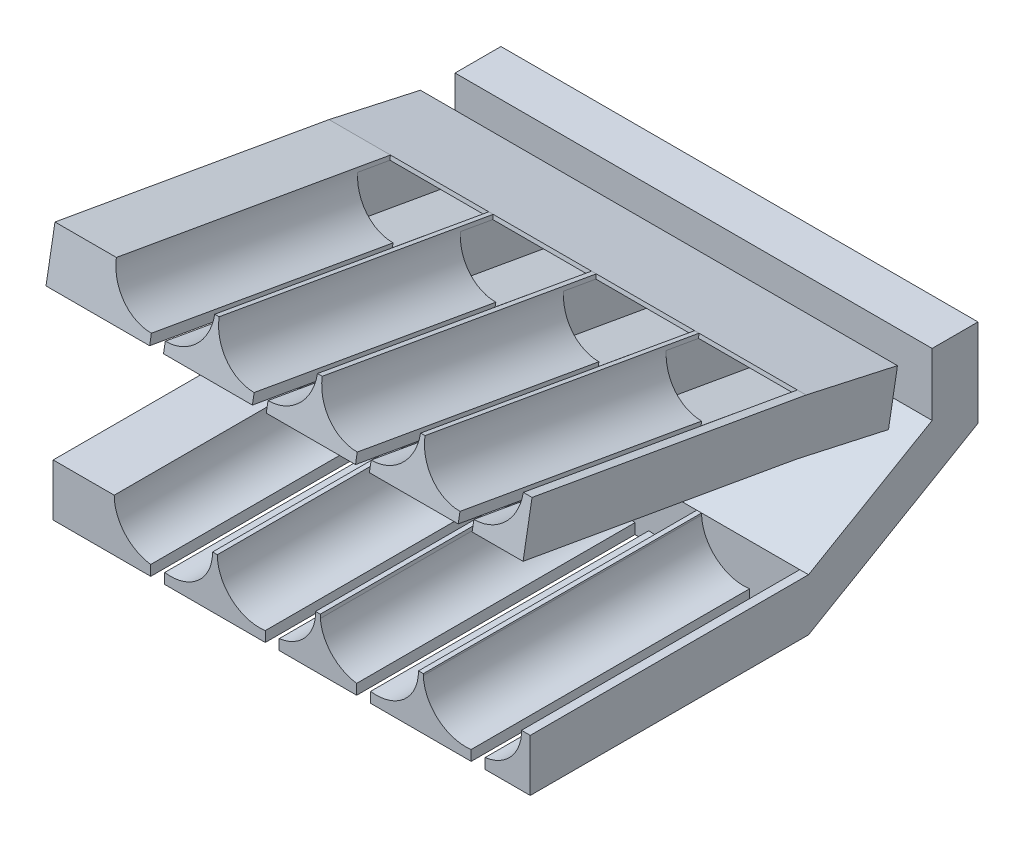
SolidWorks part; units mm, degrees
ref_plane "Front Plane" through (0, 0, 0) normal (0, 0, 1) x (1, 0, 0)
ref_plane "Top Plane" through (0, 0, 0) normal (0, 1, 0) x (1, 0, 0)
ref_plane "Right Plane" through (0, 0, 0) normal (1, 0, 0) x (0, 0, -1)
sketch "Sketch2" plane through (0, 0, 0) normal (1, 0, 0) x (0, 0, -1)
  line L1 (-68.9365, 12.1554) -> (-66.6791, 24.9579)
  line L2 (-66.6791, 24.9579) -> (2.2574, 12.8025)
  line L3 (2.2574, 12.8025) -> (0, 0)
  line L4 (0, 0) -> (-68.9365, 12.1554)
  point P3 (1.1287, 6.4013)
  dimension "D1" = 13
  dimension "D2" = 70
extrude "Boss-Extrude1" add sketch "Sketch2" along normal blind 120
sketch "Sketch4" plane through (0, 0, 0) normal (0, -0.1736, -0.9848) x (-1, 0, 0)
  line L0 (-93.0728, 13) -> (-92.5195, 13)
  line L1 (-120, 13) -> (0, 13) construction
  line L2 (-120, 0) -> (0, 0) construction
  line L3 (-105.4416, 2.5563) -> (-105.4416, 24.3801) construction
  line L4 (-107.1893, 2.5554) -> (-107.1893, 0)
  line L5 (-107.1893, 0) -> (-103.6938, 0)
  line L6 (-103.6938, 2.5554) -> (-103.6938, 0)
  line L7 (-92.5195, 13) -> (-92.5195, 3.283) construction
  line L8 (-81.3452, 2.5554) -> (-81.3452, 0)
  line L9 (-77.8497, 2.5554) -> (-77.8497, 0)
  line L10 (-77.8497, 0) -> (-81.3452, 0)
  line L11 (-67.2287, 13) -> (-66.0287, 13)
  line L12 (-66.6287, 13) -> (-66.6287, 9.1264) construction
  line L13 (-26.068, 2.5554) -> (-26.068, 0)
  line L14 (-55.4076, 2.5554) -> (-55.4076, 0)
  line L15 (-55.4076, 0) -> (-51.9121, 0)
  line L16 (-51.9121, 2.5554) -> (-51.9121, 0)
  line L17 (-40.1845, 13) -> (-40.7378, 13)
  line L18 (-29.5635, 2.5554) -> (-29.5635, 0)
  line L19 (-26.068, 0) -> (-29.5635, 0)
  line L20 (-93.0728, 13) -> (-91.9663, 13)
  line L21 (-67.2287, 13) -> (-66.0287, 13)
  line L22 (-41.291, 13) -> (-40.7378, 13)
  line L23 (-92.5195, 13) -> (-91.9663, 13)
  line L24 (-67.2287, 13) -> (-66.0287, 13)
  line L25 (-41.291, 13) -> (-40.1845, 13)
  line L26 (-15.4469, 13) -> (-14.8703, 13)
  line L30 (-14.8703, 13) -> (-14.2936, 13)
  line L31 (-14.2936, 13) -> (-0.2952, 13)
  line L34 (-14.2936, 13) -> (-0.4919, 13)
  arc A0 (-117.8104, 13) -> (-107.1893, 2.5554) centre (-107.2335, 13.133) ccw
  arc A1 (-93.0728, 13) -> (-103.6938, 2.5554) centre (-103.6496, 13.133) cw
  arc A2 (-91.9663, 13) -> (-81.3452, 2.5554) centre (-81.3894, 13.133) ccw
  arc A3 (-67.2287, 13) -> (-77.8497, 2.5554) centre (-77.8055, 13.133) cw
  arc A4 (-66.0287, 13) -> (-55.4076, 2.5554) centre (-55.4518, 13.133) ccw
  arc A5 (-41.291, 13) -> (-51.9121, 2.5554) centre (-51.8679, 13.133) cw
  arc A6 (-40.1845, 13) -> (-29.5635, 2.5554) centre (-29.6077, 13.133) ccw
  arc A7 (-15.4469, 13) -> (-26.068, 2.5554) centre (-26.0238, 13.133) cw
  point P13 (-105.4416, 0)
  line M10 (0, 13) -> (-120, 13)
  line M12 (-120, 0) -> (0, 0)
  dimension "D1" = 0.6
extrude "Cut-Extrude4" cut sketch "Sketch4" against normal through all contours A1 A0 L4 L6 M10 M12 | A3 A2 L8 L9 M10 M12 | A5 A4 L14 L16 M10 M12 | A7 A6 L18 L13 M10 M12
sketch "Sketch5" plane through (120, 0, 0) normal (1, 0, 0) x (0, 0, -1)
  line L0 (2.2574, 12.8025) -> (25.2448, 7.706)
  line L3 (2.2574, 12.8025) -> (0, 0)
  line L4 (2.2574, 12.8025) -> (0, 0)
  line L5 (25.2448, 7.706) -> (22.9874, -5.0965)
  line L7 (0, 0) -> (22.9874, -5.0965)
  line L8 (2.2574, 12.8025) -> (0, 0)
  line L9 (0, 0) -> (2.2574, 12.8025)
  line M5 (0, 0) -> (2.2574, 12.8025)
extrude "Boss-Extrude4" add sketch "Sketch5" against normal up to surface (120 mm away) contours L7 L5 L0 M5
sketch "Sketch11" plane through (0, -4.0848, -23.1658) normal (0, -0.1736, -0.9848) x (-1, 0, 0)
  line L0 (-117.8, 11.9726) -> (-117.8, 1.5726)
  line L1 (0, 11.9726) -> (-120, 11.9726) construction
  line L2 (0, -1.0274) -> (-120, -1.0274) construction
  line L3 (-117.8, 11.9726) -> (-93.1, 11.9726)
  line L4 (-93.1, 11.9726) -> (-93.1, 1.5726)
  line L5 (-91.9, 11.9726) -> (-91.9, 1.5726)
  line L6 (-91.9, 11.9726) -> (-67.2, 11.9726)
  line L7 (-67.2, 11.9726) -> (-67.2, 1.5726)
  line L8 (-66, 11.9726) -> (-66, 1.5726)
  line L9 (-66, 11.9726) -> (-41.3, 11.9726)
  line L10 (-41.3, 11.9726) -> (-41.3, 1.5726)
  line L11 (-40.1, 11.9726) -> (-40.1, 1.5726)
  line L12 (-40.1, 11.9726) -> (-15.4, 11.9726)
  line L13 (-15.4, 11.9726) -> (-15.4, 1.5726)
  line L14 (-117.8, 1.5726) -> (-93.1, 1.5726)
  line L15 (-91.9, 1.5726) -> (-67.2, 1.5726)
  line L16 (-66, 1.5726) -> (-41.3, 1.5726)
  line L17 (-40.1, 1.5726) -> (-15.4, 1.5726)
  dimension "D1" = 2.2
  dimension "D2" = 2.6
  dimension "D3" = 24.7
  dimension "D4" = 1.2
  dimension "D5" = 24.7
  dimension "D6" = 1.2
  dimension "D7" = 24.7
  dimension "D8" = 1.2
  dimension "D9" = 24.7
extrude "Cut-Extrude9" cut sketch "Sketch11" against normal blind 31.8
sketch "Sketch12" plane through (0, 12.6797, -2.8112) normal (0, 0.9763, -0.2165) x (1, 0, 0)
  line L0 (15.4469, -0.5672) -> (15.4, 22.9783)
  line L1 (15.4, 22.9783) -> (120, 22.9783)
  line L2 (120, 22.9783) -> (120, -0.5672)
  line L3 (15.4469, -0.5672) -> (120, -0.5672)
sketch "Sketch13" plane through (120, 0, 0) normal (1, 0, 0) x (0, 0, -1)
  line L6 (33.9584, 7.0963) -> (33.9584, -8.5947)
  line L7 (33.9584, -8.5947) -> (2.8725, -26.6541)
  line L8 (2.8725, -26.6541) -> (2.8725, -39.7541)
  line L9 (2.8725, -39.7541) -> (45.5009, -14.989)
  line L10 (45.5009, -14.989) -> (45.5009, 7.0963)
  line L11 (33.9584, 7.0963) -> (45.5009, 7.0963)
  dimension "D1" = 13.1
extrude "Boss-Extrude5" add sketch "Sketch13" against normal up to surface (120 mm away) separate body up to face at (0, 8.7542, 14.1877)
sketch "Sketch14" plane through (120, 0, 0) normal (1, 0, 0) x (0, 0, -1)
  line L0 (2.8725, -26.6541) -> (-67.1275, -26.6541)
  line L1 (2.8725, -39.7541) -> (-67.1275, -39.7541)
  line L2 (-67.1275, -26.6541) -> (-67.1275, -39.7541)
  line L9 (45.5009, 7.0963) -> (33.9584, 7.0963)
  line L10 (33.9584, 7.0963) -> (33.9584, -8.5947)
  line L11 (33.9584, -8.5947) -> (2.8725, -26.6541)
  line L12 (2.8725, -26.6541) -> (2.8725, -39.7541)
  line L13 (2.8725, -39.7541) -> (45.5009, -14.989)
  line L14 (45.5009, -14.989) -> (45.5009, 7.0963)
  line L18 (2.8725, -26.6541) -> (2.8725, -39.7541)
  dimension "D1" = 0
  dimension "D3" = 70
extrude "Boss-Extrude6" add sketch "Sketch14" against normal up to surface (120 mm away) up to face at (0, -12.6332, -27.4439)
sketch "Sketch15" plane through (0, 0, 67.1275) normal (0, 0, 1) x (1, 0, 0)
  line L0 (15.349, -26.6541) -> (15.349, -36.5508)
  line L1 (0, -26.6541) -> (120, -26.6541) construction
  line L2 (40.0908, -26.6541) -> (40.0908, -38.034)
  line L3 (41.2908, -26.6541) -> (41.2908, -38.034)
  line L4 (65.9908, -26.6541) -> (65.9908, -36.8974)
  line L5 (0, -26.6541) -> (120, -26.6541) construction
  line L6 (67.1908, -26.6541) -> (67.1908, -36.8974)
  line L7 (91.9, -26.6541) -> (91.9, -36.8974)
  line L8 (93.1, -26.6541) -> (93.1, -36.8974)
  line L9 (117.8, -26.6541) -> (117.8, -36.8974)
  line L10 (120, -26.6541) -> (120, -39.7541) construction
  line L11 (24.5333, -37.1534) -> (24.5333, -39.7541)
  line L12 (0, -39.7541) -> (120, -39.7541) construction
  line L13 (15.349, -26.6541) -> (40.0908, -26.6541)
  line L14 (40.6908, -26.6541) -> (40.6908, -41.861) construction
  line L15 (28.0333, -39.7541) -> (28.0333, -37.1534)
  line L16 (24.5333, -39.7541) -> (28.0333, -39.7541)
  line L17 (15.349, -26.6541) -> (40.0908, -26.6541)
  line L18 (53.3484, -39.7541) -> (53.3484, -37.1534)
  line L19 (56.8484, -37.1534) -> (56.8484, -39.7541)
  line L20 (56.8484, -39.7541) -> (53.3484, -39.7541)
  line L21 (66.0326, -26.6541) -> (41.2908, -26.6541)
  line L22 (66.5908, -26.6541) -> (66.5908, -39.7541) construction
  line L23 (76.3333, -39.7541) -> (79.8333, -39.7541)
  line L24 (79.8333, -39.7541) -> (79.8333, -37.1534)
  line L25 (76.3333, -37.1534) -> (76.3333, -39.7541)
  line L26 (67.149, -26.6541) -> (91.8908, -26.6541)
  line L27 (105.1484, -39.7541) -> (105.1484, -37.1534)
  line L28 (108.6484, -37.1534) -> (108.6484, -39.7541)
  line L29 (108.6484, -39.7541) -> (105.1484, -39.7541)
  line L30 (117.8326, -26.6541) -> (93.0908, -26.6541)
  line L31 (24.5333, -39.7541) -> (28.0333, -39.7541)
  arc A0 (15.349, -26.6541) -> (24.5333, -37.1534) centre (25.9424, -26.6541) ccw
  arc A1 (28.0333, -37.1534) -> (40.0908, -26.6541) centre (29.4908, -26.6541) ccw
  arc A2 (53.3484, -37.1534) -> (41.2908, -26.6541) centre (51.8908, -26.6541) cw
  arc A3 (66.0326, -26.6541) -> (56.8484, -37.1534) centre (55.4392, -26.6541) cw
  arc A4 (67.149, -26.6541) -> (76.3333, -37.1534) centre (77.7424, -26.6541) ccw
  arc A5 (79.8333, -37.1534) -> (91.8908, -26.6541) centre (81.2908, -26.6541) ccw
  arc A6 (105.1484, -37.1534) -> (93.0908, -26.6541) centre (103.6908, -26.6541) cw
  arc A7 (117.8326, -26.6541) -> (108.6484, -37.1534) centre (107.2392, -26.6541) cw
  line M19 (120, -26.6541) -> (0, -26.6541)
  line M21 (0, -39.7541) -> (120, -39.7541)
  dimension "D9" = 0.6
  dimension "D1" = 1.2
  dimension "D2" = 24.7
  dimension "D3" = 1.2
  dimension "D4" = 2.2
  dimension "D5" = 24.7
  dimension "D6" = 1.2
  dimension "D8" = 3.5
extrude "Cut-Extrude12" cut sketch "Sketch15" against normal up to vertex (70 mm away) contours L15 A1 A0 L11 M19 M21 | A3 L4 A2 L18 L19 M19 M21 | L24 A5 L6 A4 L25 M19 M21 | A7 L9 L8 A6 L27 L28 M19 M21 up to point (0, -26.6541, -2.8725)
